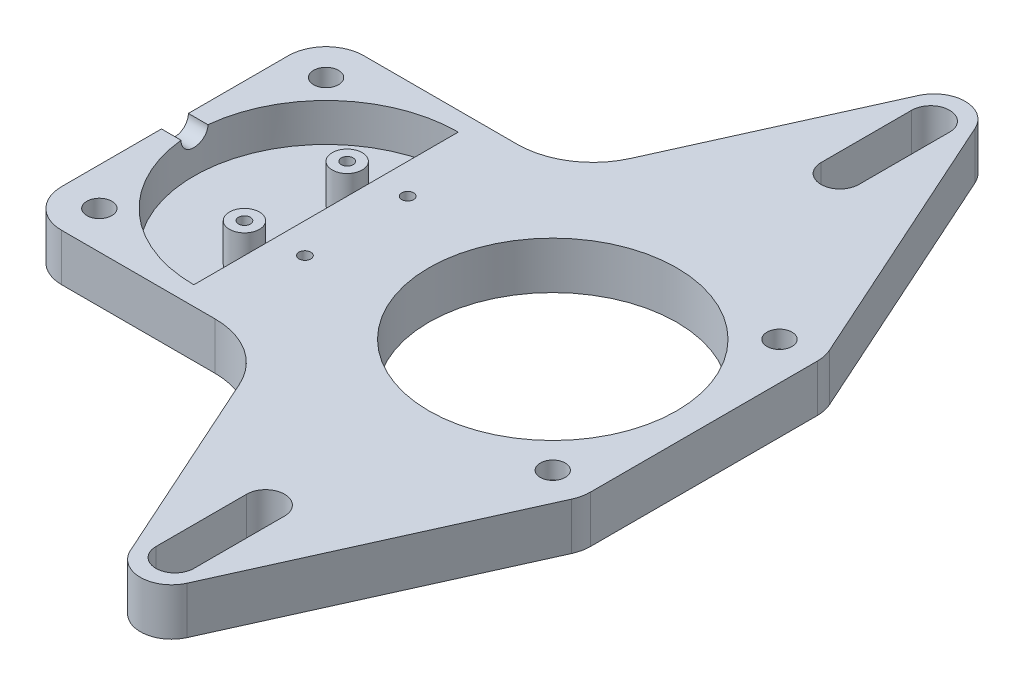
SolidWorks part; units mm, degrees
ref_plane "Front Plane" through (0, 0, 0) normal (0, 0, 1) x (1, 0, 0)
ref_plane "Top Plane" through (0, 0, 0) normal (0, 1, 0) x (1, 0, 0)
ref_plane "Right Plane" through (0, 0, 0) normal (1, 0, 0) x (0, 0, -1)
sketch "Sketch1" plane through (0, 0, 0) normal (0, 1, 0) x (1, 0, 0)
  line L0 (38.1, 19.05) -> (38.1, 25.4) construction
  line L1 (-19.05, -25.4) -> (57.15, -25.4)
  line L2 (-25.4, -19.05) -> (-25.4, 19.05)
  line L3 (-19.05, 25.4) -> (57.15, 25.4)
  line L4 (63.5, -19.05) -> (63.5, 19.05)
  line L5 (-25.4, -25.4) -> (63.5, 25.4) construction
  line L6 (-25.4, 25.4) -> (63.5, -25.4) construction
  line L7 (57.15, 0) -> (63.5, 0) construction
  line L9 (-7.62, -11.176) -> (7.62, -11.176) construction
  line L10 (-7.62, -11.176) -> (-7.62, 11.176) construction
  line L11 (-7.62, 11.176) -> (7.62, 11.176) construction
  line L12 (7.62, -11.176) -> (7.62, 11.176) construction
  line L13 (-7.62, -11.176) -> (7.62, 11.176) construction
  line L14 (-7.62, 11.176) -> (7.62, -11.176) construction
  circle A0 centre (0, 0) radius 19.05 construction
  circle A1 centre (38.1, 0) radius 19.05 construction
  circle A2 centre (38.1, 0) radius 12.7 construction
  circle A3 centre (38.1, 0) radius 20.828
  arc A4 (-25.4, 19.05) -> (-19.05, 25.4) centre (-19.05, 19.05) cw
  arc A5 (-19.05, -25.4) -> (-25.4, -19.05) centre (-19.05, -19.05) cw
  arc A6 (57.15, -25.4) -> (63.5, -19.05) centre (57.15, -19.05) ccw
  arc A7 (57.15, 25.4) -> (63.5, 19.05) centre (57.15, 19.05) cw
  circle A8 centre (-19.05, 19.05) radius 2.1
  circle A9 centre (-19.05, -19.05) radius 2.1
  circle A10 centre (57.15, -19.05) radius 2.1
  circle A11 centre (57.15, 19.05) radius 2.1
  point P6 (19.05, 0)
  dimension "D1" = 38.1
  dimension "D2" = 38.1
  dimension "D3" = 50.8
  dimension "D7" = 25.4
  dimension "D8" = 41.656
  dimension "D9" = 6.35
  dimension "D10" = 4.2
  dimension "D4" = 88.9
  dimension "D5" = 15.24
  dimension "D6" = 22.352
extrude "Boss-Extrude1" add sketch "Sketch1" along normal blind 7.9248
sketch "Sketch2" plane through (0, 7.9248, 0) normal (0, 1, 0) x (1, 0, 0)
  line L0 (0, 22.225) -> (38.1, 22.225)
  line L1 (38.1, -22.225) -> (0, -22.225)
  arc A0 (0, 22.225) -> (0, -22.225) centre (0, 0) ccw
  arc A1 (38.1, -22.225) -> (38.1, 22.225) centre (38.1, 0) ccw
  dimension "D1" = 44.45
extrude "Cut-Extrude1" cut sketch "Sketch2" against normal offset from surface (6.4008 mm away) 1.524 up to face at (57.15, 0, 21.15)
sketch "Sketch3" plane through (0, 1.524, 0) normal (0, 1, 0) x (1, 0, 0)
  line L0 (0, 0) -> (0, 50000) construction
  line L1 (-7.62, -11.176) -> (7.62, -11.176) construction
  line L2 (-7.62, -11.176) -> (-7.62, 11.176) construction
  line L3 (-7.62, 11.176) -> (7.62, 11.176) construction
  line L4 (7.62, -11.176) -> (7.62, 11.176) construction
  line L5 (-7.62, -11.176) -> (7.62, 11.176) construction
  line L6 (-7.62, 11.176) -> (7.62, -11.176) construction
  line L7 (0, 0) -> (50000, 0) construction
  circle A0 centre (5.08, 8.636) radius 0.997
  circle A1 centre (5.08, -8.636) radius 0.997
  circle A2 centre (-5.08, 8.636) radius 0.997
  circle A3 centre (-5.08, -8.636) radius 0.997
  circle A4 centre (-5.08, 8.636) radius 2.521
  circle A5 centre (5.08, 8.636) radius 2.521
  circle A6 centre (5.08, -8.636) radius 2.521
  circle A7 centre (-5.08, -8.636) radius 2.521
  point P0 (0, 0)
  dimension "D3" = 2.54
  dimension "D4" = 2.54
  dimension "D5" = 1.9939
  dimension "D6" = 1.524
  dimension "D1" = 22.352
  dimension "D2" = 15.24
extrude "Boss-Extrude2" add sketch "Sketch3" along normal up to surface (6.4008 mm away) up to face at (19.05, 7.9248, 0)
sketch "Sketch4" plane through (0, 1.524, 0) normal (0, 1, 0) x (1, 0, 0)
  circle A0 centre (-5.08, -8.636) radius 0.9969 construction
  circle A1 centre (5.08, -8.636) radius 0.9969
  circle A2 centre (5.08, -8.636) radius 0.997
  circle A3 centre (5.08, 8.636) radius 0.9969 construction
  circle A4 centre (-5.08, 8.636) radius 0.9969 construction
  circle A5 centre (-5.08, -8.636) radius 0.997
  circle A6 centre (5.08, 8.636) radius 0.997
  circle A7 centre (-5.08, 8.636) radius 0.997
  dimension "D1" = 0
extrude "Cut-Extrude2" cut sketch "Sketch4" against normal through all
sketch "Sketch5" plane through (0, 1.524, 0) normal (0, 1, 0) x (1, 0, 0)
  line L0 (0, 22.225) -> (0, -22.225)
  line L1 (38.1, 22.225) -> (0, 22.225) construction
  line L2 (0, -22.225) -> (38.1, -22.225) construction
  line L3 (38.1, 22.225) -> (0, 22.225)
  line L4 (0, -22.225) -> (38.1, -22.225)
  circle A0 centre (38.1, 0) radius 20.828 construction
  circle A2 centre (38.1, 0) radius 20.828
  arc A3 (38.1, -22.225) -> (38.1, 22.225) centre (38.1, 0) ccw
  circle A4 centre (5.08, -8.636) radius 0.9969 construction
  circle A5 centre (5.08, 8.636) radius 0.9969 construction
  circle A6 centre (5.08, -8.636) radius 0.997
  circle A7 centre (5.08, 8.636) radius 0.997
  arc A8 (38.1, -22.225) -> (38.1, 22.225) centre (38.1, 0) ccw construction
extrude "Boss-Extrude3" add sketch "Sketch5" along normal up to surface (6.4008 mm away) up to face at (19.05, 7.9248, 0)
sketch "Sketch6" plane through (0, 0, 0) normal (0, -1, 0) x (1, 0, 0)
  line L0 (38.1, 0) -> (0, 0) construction
  line L1 (38.1, 0) -> (38.1, 50000) construction
  line L2 (57.15, -25.4) -> (-19.05, -25.4) construction
  line L5 (42.8625, 66.2173) -> (62.9395, 21.6586)
  line L6 (41.3079, 69.6277) -> (34.8921, 69.6277) construction
  line L7 (34.8921, 69.6277) -> (31.6842, 64.0715) construction
  line L8 (31.6842, 64.0715) -> (34.8921, 58.5152) construction
  line L9 (34.8921, 58.5152) -> (41.3079, 58.5152) construction
  line L10 (41.3079, 58.5152) -> (44.5158, 64.0715) construction
  line L11 (44.5158, 64.0715) -> (41.3079, 69.6277) construction
  line L12 (33.3375, 66.2173) -> (14.9455, 25.4)
  line L13 (57.15, 25.4) -> (14.9455, 25.4)
  line L14 (44.5158, -64.0715) -> (41.3079, -69.6277) construction
  line L15 (41.3079, -58.5152) -> (44.5158, -64.0715) construction
  line L16 (34.8921, -58.5152) -> (41.3079, -58.5152) construction
  line L17 (31.6842, -64.0715) -> (34.8921, -58.5152) construction
  line L18 (34.8921, -69.6277) -> (31.6842, -64.0715) construction
  line L19 (41.3079, -69.6277) -> (34.8921, -69.6277) construction
  line L20 (57.15, -25.4) -> (14.9455, -25.4)
  line L21 (33.3375, -66.2173) -> (14.9455, -25.4)
  line L22 (42.8625, -66.2173) -> (62.9395, -21.6586)
  arc A2 (42.8625, 66.2173) -> (38.1, 69.2951) centre (38.1, 64.0715) ccw
  arc A3 (33.3375, 66.2173) -> (38.1, 69.2951) centre (38.1, 64.0715) cw
  circle A10 centre (38.1, 64.0715) radius 6.4158 construction
  arc A11 (63.5, 19.05) -> (57.15, 25.4) centre (57.15, 19.05) ccw construction
  arc A12 (62.9395, 21.6586) -> (57.15, 25.4) centre (57.15, 19.05) ccw
  circle A13 centre (38.1, -64.0715) radius 6.4158 construction
  arc A14 (62.9395, -21.6586) -> (57.15, -25.4) centre (57.15, -19.05) cw
  arc A15 (33.3375, -66.2173) -> (38.1, -69.2951) centre (38.1, -64.0715) ccw
  arc A16 (42.8625, -66.2173) -> (38.1, -69.2951) centre (38.1, -64.0715) cw
  point P21 (38.1, 25.4)
  point P41 (38.1, -25.4)
  dimension "D1" = 9.525
  dimension "D2" = 65.744
  dimension "D5" = 11.1125
extrude "Boss-Extrude4" add sketch "Sketch6" against normal up to surface (7.9248 mm away) up to face at (-11.1125, 7.9248, 0)
sketch "Sketch7" plane through (-25.4, 0, 0) normal (-1, 0, 0) x (0, 0, 1)
  line L0 (-19.05, 7.9248) -> (19.05, 7.9248) construction
  circle A0 centre (0, 7.9248) radius 2.2606
  dimension "D1" = 4.5212
extrude "Cut-Extrude3" cut sketch "Sketch7" against normal up to next
sketch "Sketch8" plane through (0, 0, 0) normal (0, -1, 0) x (1, 0, 0)
  line L1 (-17.0004, 22.6) -> (-21.0996, 22.6)
  line L2 (-21.0996, 22.6) -> (-23.1492, 19.05)
  line L3 (-23.1492, 19.05) -> (-21.0996, 15.5)
  line L4 (-21.0996, 15.5) -> (-17.0004, 15.5)
  line L5 (-17.0004, 15.5) -> (-14.9508, 19.05)
  line L6 (-14.9508, 19.05) -> (-17.0004, 22.6)
  line L7 (-17.0004, -15.5) -> (-21.0996, -15.5)
  line L8 (-21.0996, -15.5) -> (-23.1492, -19.05)
  line L9 (-23.1492, -19.05) -> (-21.0996, -22.6)
  line L10 (-21.0996, -22.6) -> (-17.0004, -22.6)
  line L11 (-17.0004, -22.6) -> (-14.9508, -19.05)
  line L12 (-14.9508, -19.05) -> (-17.0004, -15.5)
  line L13 (59.1996, -15.5) -> (55.1004, -15.5)
  line L14 (55.1004, -15.5) -> (53.0508, -19.05)
  line L15 (53.0508, -19.05) -> (55.1004, -22.6)
  line L16 (55.1004, -22.6) -> (59.1996, -22.6)
  line L17 (59.1996, -22.6) -> (61.2492, -19.05)
  line L18 (61.2492, -19.05) -> (59.1996, -15.5)
  line L19 (59.1996, 22.6) -> (55.1004, 22.6)
  line L20 (55.1004, 22.6) -> (53.0508, 19.05)
  line L21 (53.0508, 19.05) -> (55.1004, 15.5)
  line L22 (55.1004, 15.5) -> (59.1996, 15.5)
  line L23 (59.1996, 15.5) -> (61.2492, 19.05)
  line L24 (61.2492, 19.05) -> (59.1996, 22.6)
  circle A0 centre (-19.05, 19.05) radius 3.55 construction
  circle A1 centre (-19.05, -19.05) radius 3.55 construction
  circle A2 centre (57.15, -19.05) radius 3.55 construction
  circle A3 centre (57.15, 19.05) radius 3.55 construction
  dimension "D1" = 7.1
extrude "Cut-Extrude4" cut sketch "Sketch8" against normal blind 5
fillet "Fillet1" radius 12.7 2 edges at (14.9455, 3.9624, -25.4) (14.9455, 3.9624, 25.4)
sketch "Sketch9" plane through (0, 7.9248, 0) normal (0, 1, 0) x (1, 0, 0)
  line L0 (34.9123, -63.5) -> (34.9123, -48.26)
  line L1 (41.2877, -63.5) -> (41.2877, -48.26)
  line L2 (38.1, -48.26) -> (38.1, -63.5) construction
  line L3 (57.15, -19.05) -> (57.15, 19.05) construction
  line L4 (-55, 0) -> (55, 0) construction
  line L5 (38.1, 48.26) -> (38.1, 63.5) construction
  line L6 (41.2877, 63.5) -> (41.2877, 48.26)
  line L7 (34.9123, 63.5) -> (34.9123, 48.26)
  line L8 (38.1, 0) -> (38.1, -63.5) construction
  arc A0 (34.9123, -63.5) -> (41.2877, -63.5) centre (38.1, -63.5) ccw
  arc A1 (34.9123, -48.26) -> (41.2877, -48.26) centre (38.1, -48.26) cw
  arc A2 (34.9123, 48.26) -> (41.2877, 48.26) centre (38.1, 48.26) ccw
  arc A3 (34.9123, 63.5) -> (41.2877, 63.5) centre (38.1, 63.5) cw
  point P11 (38.1, -55.88)
  point P21 (38.1, 55.88)
  dimension "D1" = 3.1877
  dimension "D2" = 3.1877
  dimension "D4" = 111.76
  dimension "D3" = 15.24
extrude "Cut-Extrude5" cut sketch "Sketch9" against normal blind 60.706
